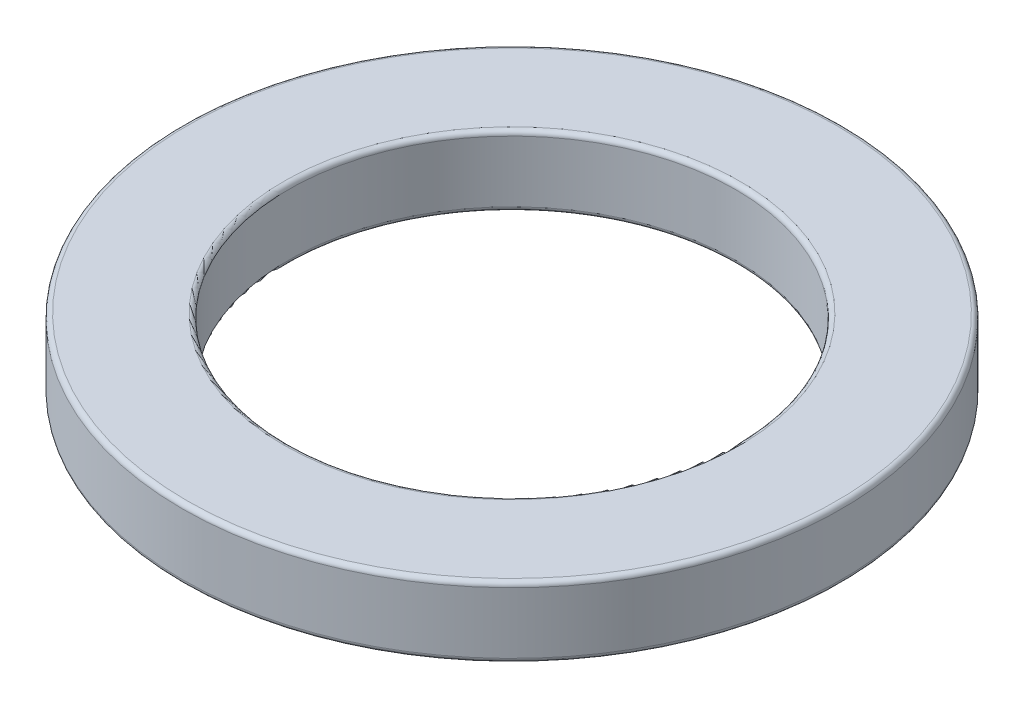
SolidWorks part; units mm, degrees
ref_plane "Front Plane" through (0, 0, 0) normal (0, 0, 1) x (1, 0, 0)
ref_plane "Top Plane" through (0, 0, 0) normal (0, 1, 0) x (1, 0, 0)
ref_plane "Right Plane" through (0, 0, 0) normal (1, 0, 0) x (0, 0, -1)
sketch "Sketch1" plane through (0, 0, 0) normal (0, 1, 0) x (1, 0, 0)
  circle A0 centre (0, 0) radius 9.5
  circle A1 centre (0, 0) radius 14
  dimension "D1" = 19
  dimension "D2" = 28
extrude "Boss-Extrude1" add sketch "Sketch1" along normal blind 3
fillet "Fillet1" radius 0.2 4 edges at (0, 0, 9.5) (0, 0, 14) (0, 3, 9.5) (0, 3, 14)
